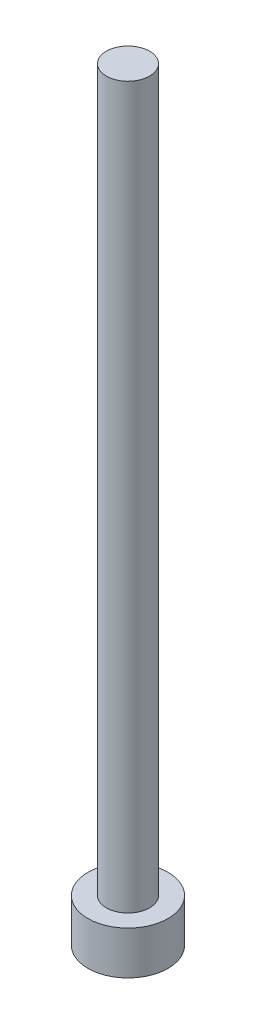
SolidWorks part; units mm, degrees
ref_plane "Front Plane" through (0, 0, 0) normal (0, 0, 1) x (1, 0, 0)
ref_plane "Top Plane" through (0, 0, 0) normal (0, 1, 0) x (1, 0, 0)
ref_plane "Right Plane" through (0, 0, 0) normal (1, 0, 0) x (0, 0, -1)
sketch "Sketch1" plane through (0, 0, 0) normal (0, 1, 0) x (1, 0, 0)
  circle A0 centre (0, 0) radius 2.78
  dimension "D1" = 5.56
extrude "Boss-Extrude1" add sketch "Sketch1" along normal blind 3
sketch "Sketch2" plane through (0, 3, 0) normal (0, 1, 0) x (1, 0, 0)
  circle A0 centre (0, 0) radius 1.5
  dimension "D1" = 3
extrude "Boss-Extrude2" add sketch "Sketch2" along normal blind 50
